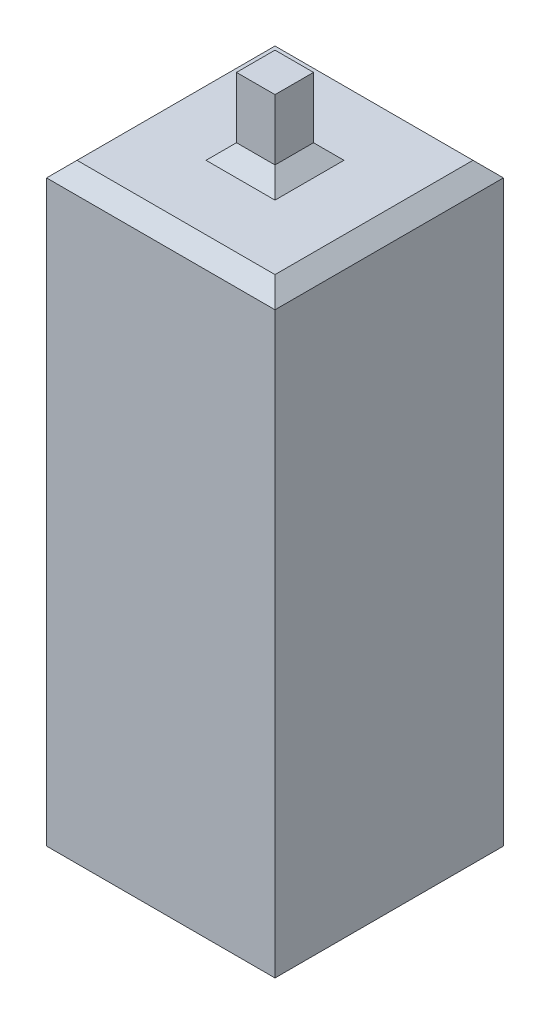
SolidWorks part; units mm, degrees
ref_plane "Front Plane" through (0, 0, 0) normal (0, 0, 1) x (1, 0, 0)
ref_plane "Top Plane" through (0, 0, 0) normal (0, 1, 0) x (1, 0, 0)
ref_plane "Right Plane" through (0, 0, 0) normal (1, 0, 0) x (0, 0, -1)
sketch "Sketch1" plane through (0, 0, 0) normal (0, 1, 0) x (1, 0, 0)
  line L1 (-150, 150) -> (150, 150)
  line L2 (-150, 150) -> (-150, -150)
  line L3 (-150, -150) -> (150, -150)
  line L4 (150, 150) -> (150, -150)
  line L5 (-150, 150) -> (150, -150) construction
  line L6 (-150, -150) -> (150, 150) construction
  point P0 (0, 0)
  point P6 (-8.6107, -8.6107)
extrude "Boss-Extrude1" add sketch "Sketch1" along normal blind 800
sketch "Sketch2" plane through (0, 800, 0) normal (0, 1, 0) x (1, 0, 0)
  line L1 (-25.2984, 25.2984) -> (25.2984, 25.2984)
  line L2 (-25.2984, 25.2984) -> (-25.2984, -25.2984)
  line L3 (-25.2984, -25.2984) -> (25.2984, -25.2984)
  line L4 (25.2984, 25.2984) -> (25.2984, -25.2984)
  line L5 (-25.2984, 25.2984) -> (25.2984, -25.2984) construction
  line L6 (-25.2984, -25.2984) -> (25.2984, 25.2984) construction
  point P0 (0, 0)
  point P6 (25.5968, -25.5968)
extrude "Boss-Extrude2" add sketch "Sketch2" along normal blind 100
chamfer "Chamfer1" distance 20 angle 45 12 edges at (0, 0, -150) (-150, 0, 0) (0, 0, 150) (150, 0, 0) (0, 800, 150) (-150, 800, 0) (0, 800, -150) (150, 800, 0) (0, 800, -25.2984) (-25.2984, 800, 0) (0, 800, 25.2984) (25.2984, 800, 0)
